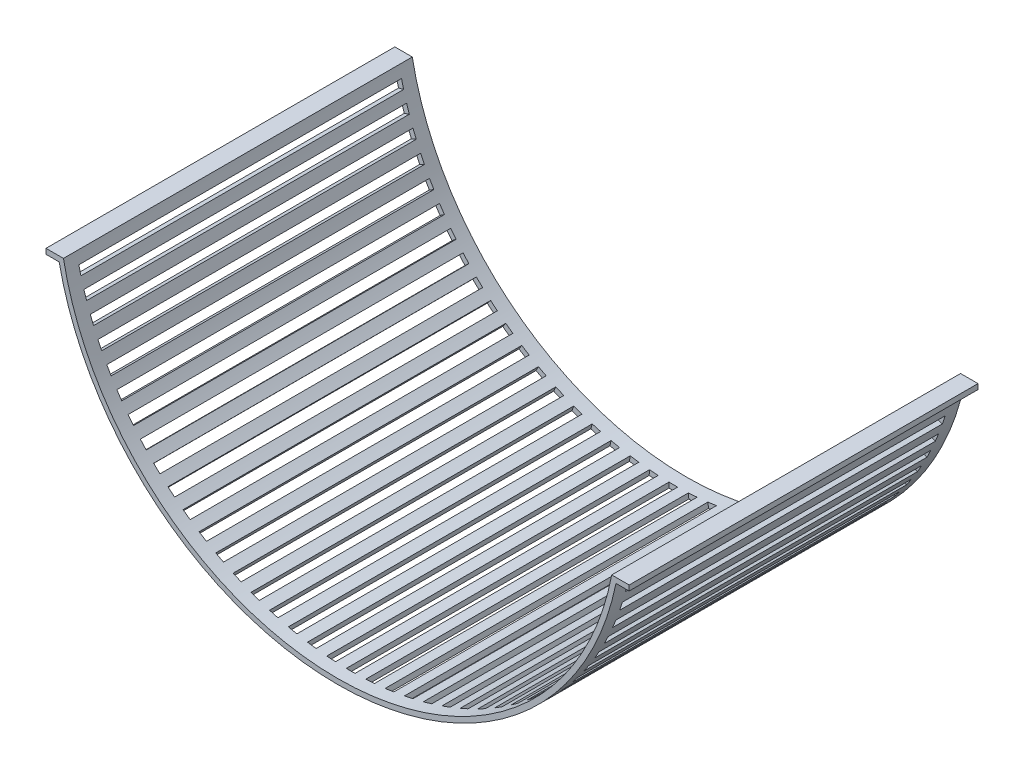
SolidWorks part; units mm, degrees
ref_plane "Front Plane" through (0, 0, 0) normal (0, 0, 1) x (1, 0, 0)
ref_plane "Top Plane" through (0, 0, 0) normal (0, 1, 0) x (1, 0, 0)
ref_plane "Right Plane" through (0, 0, 0) normal (1, 0, 0) x (0, 0, -1)
sketch "Sketch2" plane through (0, 0, 0) normal (0, 0, 1) x (1, 0, 0)
  line L0 (-167.1623, 0) -> (-157.1623, 0)
  line L1 (157.1623, 0) -> (167.1623, 0)
  line L2 (-167.1623, -3) -> (-159.6246, -3)
  line L3 (159.6246, -3) -> (167.1623, -3)
  line L4 (-167.1623, 0) -> (-167.1623, -3)
  line L5 (167.1623, 0) -> (167.1623, -3)
  arc A0 (-157.1623, 0) -> (157.1623, 0) centre (0, 30) ccw
  arc A1 (-159.6246, -3) -> (159.6246, -3) centre (0, 30) ccw
  point P5 (0, -130)
  dimension "D2" = 160
  dimension "D1" = 10
  dimension "D3" = 130
  dimension "D4" = 3
extrude "Boss-Extrude1" add sketch "Sketch2" along normal mid plane 200
sketch "Sketch3" plane through (0, 0, 0) normal (0, 1, 0) x (1, 0, 0)
  line L1 (-2.5, -92.5) -> (2.5, -92.5)
  line L2 (-2.5, -92.5) -> (-2.5, 92.5)
  line L3 (-2.5, 92.5) -> (2.5, 92.5)
  line L4 (2.5, -92.5) -> (2.5, 92.5)
  line L5 (-2.5, -92.5) -> (2.5, 92.5) construction
  line L6 (-2.5, 92.5) -> (2.5, -92.5) construction
  point P0 (0, 0)
  dimension "D1" = 5
  dimension "D2" = 185
extrude "Cut-Extrude1" cut sketch "Sketch3" against normal blind 200
pattern_circular "CirPattern1" count 90 over 360 about axis through (0, 30, 0) along (0, 0, 1) skipping 20, 70 of "Cut-Extrude1"
